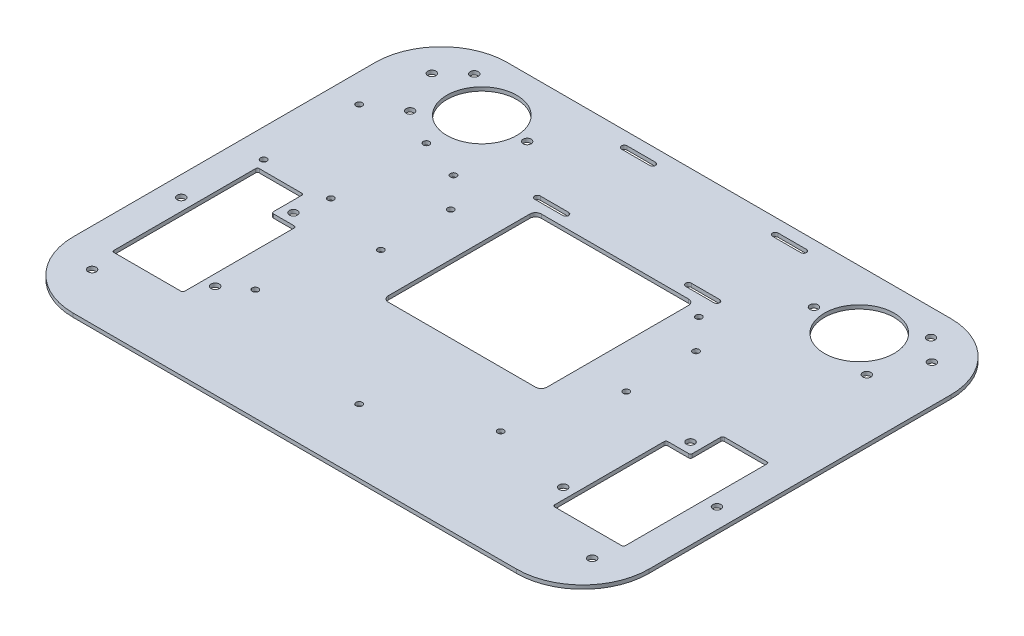
SolidWorks part; units mm, degrees
ref_plane "Front Plane" through (0, 0, 0) normal (0, 0, 1) x (1, 0, 0)
ref_plane "Top Plane" through (0, 0, 0) normal (0, 1, 0) x (1, 0, 0)
ref_plane "Right Plane" through (0, 0, 0) normal (1, 0, 0) x (0, 0, -1)
sketch "Sketch1" plane through (0, 0, 0) normal (0, 1, 0) x (1, 0, 0)
  line L0 (0, 115) -> (0, 0) construction
  line L5 (117.5, -115) -> (-117.5, -115)
  line L6 (152.5, -80) -> (152.5, 80)
  line L7 (117.5, 115) -> (-117.5, 115)
  line L8 (-152.5, -80) -> (-152.5, 80)
  line L9 (0, 0) -> (152.5, 0) construction
  line L10 (-117.5, 80) -> (117.5, 80) construction
  arc A4 (117.5, 115) -> (152.5, 80) centre (117.5, 80) cw
  arc A5 (152.5, -80) -> (117.5, -115) centre (117.5, -80) cw
  arc A6 (-117.5, -115) -> (-152.5, -80) centre (-117.5, -80) cw
  arc A7 (-152.5, 80) -> (-117.5, 115) centre (-117.5, 80) cw
  point P0 (0, 0)
  dimension "D3" = 230
  dimension "D1" = 35
  dimension "D2" = 305
  dimension "D4" = 235
ref_plane "Plane1" through (0, -40, 0) normal (0, 1, 0) x (1, 0, 0)
sketch "Sketch2" plane through (0, 0, 0) normal (0, 1, 0) x (1, 0, 0)
  line L0 (98, -76.4) -> (98, -16.4)
  line L1 (98, -16.4) -> (111, -16.4)
  line L2 (111, -16.4) -> (111, 0.6)
  line L3 (111, 0.6) -> (135.5, 0.6)
  line L4 (135.5, 0.6) -> (135.5, -76.4)
  line L5 (135.5, -76.4) -> (98, -76.4)
  dimension "D1" = 37.5
  dimension "D2" = 77
  dimension "D3" = 13
  dimension "D4" = 60
  dimension "D5" = 98
  dimension "D6" = 16.4
sketch "Sketch3" plane through (0, 0, 0) normal (0, 1, 0) x (1, 0, 0)
  line L2 (111, -16.4) -> (111, 0.6) construction
  line L3 (98, -16.4) -> (111, -16.4) construction
  circle A0 centre (92.2, -65.0702) radius 2.15
  circle A1 centre (105.2, -10.6) radius 2.15
  circle A2 centre (141.9358, -33.3314) radius 2.15
  dimension "D1" = 4.3
  dimension "D4" = 59
  dimension "D5" = 13
  dimension "D7" = 5.8
  dimension "D6" = 5.8
  dimension "D2" = 56
  dimension "D3" = 43.2
sketch "Sketch8" plane through (0, 0, 0) normal (0, 1, 0) x (1, 0, 0)
  line L1 (-132.5, -90) -> (132.5, -90) construction
  line L2 (-132.5, -90) -> (-132.5, 90) construction
  line L3 (-132.5, 90) -> (132.5, 90) construction
  line L4 (132.5, -90) -> (132.5, 90) construction
  line L5 (-132.5, -90) -> (132.5, 90) construction
  line L6 (-132.5, 90) -> (132.5, -90) construction
  circle A0 centre (-132.5, 90) radius 2.15
  circle A1 centre (132.5, 90) radius 2.15
  circle A2 centre (-132.5, -90) radius 2.15
  circle A3 centre (132.5, -90) radius 2.15
  point P0 (0, 0)
  dimension "D1" = 4.3
  dimension "D2" = 265
  dimension "D3" = 180
extrude "Boss-Extrude1" add sketch "Sketch1" against normal blind 2
extrude "Cut-Extrude8" cut sketch "Sketch2" against normal through all
extrude "Cut-Extrude9" cut sketch "Sketch3" against normal through all
extrude "Cut-Extrude11" cut sketch "Sketch8" against normal through all
fillet "Fillet1" radius 1 6 edges at (98, -1, 76.4) (135.5, -1, 76.4) (135.5, -1, -0.6) (98, -1, 16.4) (111, -1, 16.4) (111, -1, -0.6)
sketch "Sketch17" plane through (0, 0, 0) normal (0, 1, 0) x (1, 0, 0)
  line L0 (100, 84) -> (100, 0) construction
  line L1 (121, 67) -> (79, 67) construction
  line L2 (121, 67) -> (121, 101) construction
  line L3 (121, 101) -> (79, 101) construction
  line L4 (79, 67) -> (79, 101) construction
  line L5 (121, 67) -> (79, 101) construction
  line L6 (121, 101) -> (79, 67) construction
  line L7 (117.5, 115) -> (-117.5, 115) construction
  line L8 (100, 0) -> (0, 0) construction
  line L9 (100, 84) -> (76, 84) construction
  circle A0 centre (100, 84) radius 18.5
  circle A1 centre (121, 101) radius 2.15
  circle A4 centre (121, 67) radius 2.15
  circle A5 centre (-132.5, 90) radius 3.5 construction
  circle A6 centre (76, 84) radius 2.15
  dimension "D2" = 37
  dimension "D3" = 4.3
  dimension "D8" = 7
  dimension "D9" = 24
  dimension "D1" = 42
  dimension "D4" = 84
  dimension "D5" = 14
  dimension "D6" = 100
  dimension "D7" = 34
extrude "Cut-Extrude19" cut sketch "Sketch17" against normal blind 10
sketch "Sketch19" plane through (0, 0, 0) normal (0, 1, 0) x (1, 0, 0)
  line L0 (0, 14) -> (0, 0) construction
  line L1 (-42, -26.5) -> (42, -26.5)
  line L2 (-42, -26.5) -> (-42, 54.5)
  line L3 (-42, 54.5) -> (42, 54.5)
  line L4 (42, -26.5) -> (42, 54.5)
  line L5 (-42, -26.5) -> (42, 54.5) construction
  line L6 (-42, 54.5) -> (42, -26.5) construction
  line L8 (65, -4.5) -> (-65, -4.5) construction
  line L9 (65, -4.5) -> (65, 32.5) construction
  line L10 (65, 32.5) -> (-65, 32.5) construction
  line L11 (-65, -4.5) -> (-65, 32.5) construction
  line L12 (65, -4.5) -> (-65, 32.5) construction
  line L13 (65, 32.5) -> (-65, -4.5) construction
  circle A0 centre (-65, 32.5) radius 1.65
  circle A1 centre (-65, -4.5) radius 1.65
  circle A2 centre (65, -4.5) radius 1.65
  circle A3 centre (65, 32.5) radius 1.65
  point P0 (0, 14)
  dimension "D6" = 3.3
  dimension "D1" = 81
  dimension "D2" = 84
  dimension "D3" = 14
  dimension "D4" = 130
  dimension "D5" = 37
extrude "Cut-Extrude21" cut sketch "Sketch19" against normal through all
fillet "Fillet2" radius 3 4 edges at (-42, -1, 26.5) (42, -1, 26.5) (42, -1, -54.5) (-42, -1, -54.5)
sketch "Sketch20" plane through (0, 0, 0) normal (0, 1, 0) x (1, 0, 0)
  line L0 (-152.5, 80) -> (-152.5, -80) construction
  line L1 (-101.9, 5.9) -> (-137.5, 5.9) construction
  line L2 (-101.9, 5.9) -> (-101.9, 56.5) construction
  line L3 (-101.9, 56.5) -> (-137.5, 56.5) construction
  line L4 (-137.5, 5.9) -> (-137.5, 56.5) construction
  line L5 (-101.9, 5.9) -> (-137.5, 56.5) construction
  line L6 (-101.9, 56.5) -> (-137.5, 5.9) construction
  line L7 (117.5, 115) -> (-117.5, 115) construction
  circle A0 centre (-137.5, 56.5) radius 1.65
  circle A1 centre (-101.9, 56.5) radius 1.65
  circle A2 centre (-137.5, 5.9) radius 1.65
  circle A3 centre (-101.9, 5.9) radius 1.65
  point P0 (-119.7, 31.2)
  dimension "D3" = 3.3
  dimension "D1" = 35.6
  dimension "D2" = 15
  dimension "50.3" = 50.6
  dimension "D4" = 58.5
extrude "Cut-Extrude22" cut sketch "Sketch20" against normal through all
sketch "Sketch21" plane through (0, 0, 0) normal (0, 1, 0) x (1, 0, 0)
  line L1 (-80, 49) -> (50, 49) construction
  line L2 (-80, 49) -> (-80, -56) construction
  line L3 (-80, -56) -> (50, -56) construction
  line L4 (50, 49) -> (50, -56) construction
  circle A0 centre (-80, 49) radius 1.65
  circle A1 centre (-80, -56) radius 1.65
  circle A2 centre (0, -81) radius 1.65
  circle A3 centre (50, -56) radius 1.65
  circle A4 centre (50, 49) radius 1.65
  dimension "D4" = 49
  dimension "D5" = 25
  dimension "D7" = 50
  dimension "D8" = 3.3
  dimension "D1" = 80
  dimension "D2" = 50
  dimension "D3" = 105
  dimension "D6" = 130
extrude "Cut-Extrude23" cut sketch "Sketch21" against normal through all
sketch "Sketch23" plane through (0, 0, 0) normal (0, 1, 0) x (1, 0, 0)
  line L0 (117.5, 115) -> (-117.5, 115) construction
  line L1 (32.5, 105.5) -> (47.5, 105.5)
  line L2 (32.5, 105.5) -> (32.5, 108.5) construction
  line L3 (32.5, 108.5) -> (47.5, 108.5)
  line L4 (47.5, 105.5) -> (47.5, 108.5) construction
  line L5 (32.5, 105.5) -> (47.5, 108.5) construction
  line L6 (32.5, 108.5) -> (47.5, 105.5) construction
  line L7 (32.5, 61) -> (47.5, 61) construction
  line L8 (32.5, 62.5) -> (47.5, 62.5)
  line L9 (32.5, 59.5) -> (47.5, 59.5)
  line L10 (40, 107) -> (40, 61) construction
  arc A0 (47.5, 108.5) -> (47.5, 105.5) centre (47.5, 107) cw
  arc A1 (32.5, 108.5) -> (32.5, 105.5) centre (32.5, 107) ccw
  arc A2 (32.5, 62.5) -> (32.5, 59.5) centre (32.5, 61) ccw
  arc A3 (47.5, 59.5) -> (47.5, 62.5) centre (47.5, 61) ccw
  point P0 (40, 107)
  point P10 (40, 61)
  dimension "D1" = 6.5
  dimension "D2" = 15
  dimension "D3" = 3
  dimension "D4" = 40
  dimension "D5" = 43
extrude "Cut-Extrude24" cut sketch "Sketch23" against normal through all
mirror "Mirror1" about plane through (0, 0, 0) normal (1, 0, 0) of "Cut-Extrude24", "Fillet1", "Cut-Extrude8", "Cut-Extrude9", "Cut-Extrude19"
